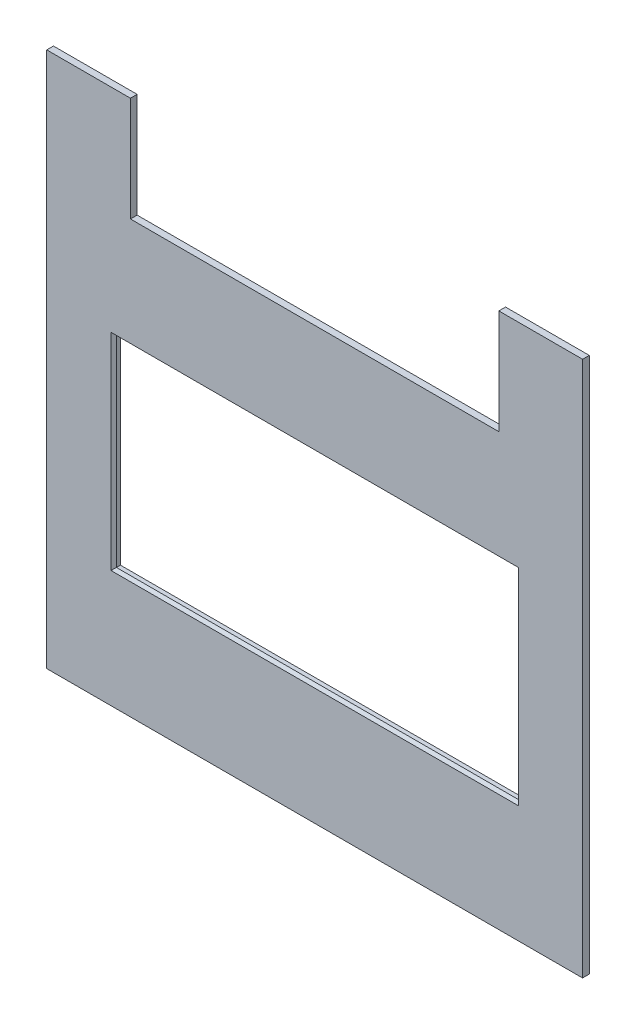
SolidWorks part; units mm, degrees
ref_plane "Plan de face" through (0, 0, 0) normal (0, 0, 1) x (1, 0, 0)
ref_plane "Plan de dessus" through (0, 0, 0) normal (0, 1, 0) x (1, 0, 0)
ref_plane "Plan de droite" through (0, 0, 0) normal (1, 0, 0) x (0, 0, -1)
sketch "Esquisse1" plane through (0, 0, 0) normal (0, 0, 1) x (1, 0, 0)
  line L1 (-200, 200) -> (200, 200)
  line L2 (-200, 200) -> (-200, -200)
  line L3 (-200, -200) -> (200, -200)
  line L4 (200, 200) -> (200, -200)
  line L5 (-200, 200) -> (200, -200) construction
  line L6 (-200, -200) -> (200, 200) construction
  point P0 (0, 0)
  dimension "D1" = 400
  dimension "D2" = 400
extrude "Boss.-Extru.1" add sketch "Esquisse1" along normal blind 5
sketch "Esquisse2" plane through (0, 0, 5) normal (0, 0, 1) x (1, 0, 0)
  line L0 (0, -230.2688) -> (0, 301.6087) construction
  line L1 (200, 200) -> (-200, 200) construction
  line L2 (-150, 39.43) -> (150, 39.43)
  line L3 (-150, 39.43) -> (-150, -110.59)
  line L4 (-150, -110.59) -> (150, -110.59)
  line L5 (150, 39.43) -> (150, -110.59)
  line L6 (-150, 39.43) -> (150, -110.59) construction
  line L7 (-150, -110.59) -> (150, 39.43) construction
  point P3 (0, -35.58)
  dimension "D1" = 235.58
  dimension "D2" = 300
  dimension "D3" = 150.02
extrude "Enlèv. mat.-Extru.1" cut sketch "Esquisse2" against normal blind 10
chamfer "Chanfrein1" distance 2 angle 45 4 edges at (0, 39.43, 5) (150, -35.58, 5) (0, -110.59, 5) (-150, -35.58, 5)
sketch "Esquisse3" plane through (0, 0, 5) normal (0, 0, 1) x (1, 0, 0)
  line L0 (0, 0) -> (0, 395.7632) construction
  line L2 (-137.5, 200) -> (137.5, 200)
  line L3 (-137.5, 200) -> (-137.5, 121.9316)
  line L4 (-137.5, 121.9316) -> (137.5, 121.9316)
  line L5 (137.5, 200) -> (137.5, 121.9316)
  line L6 (-137.5, 200) -> (137.5, 121.9316) construction
  line L7 (-137.5, 121.9316) -> (137.5, 200) construction
  line L8 (200, 200) -> (-200, 200) construction
  point P3 (0, 160.9658)
  dimension "D2" = 275
extrude "Enlèv. mat.-Extru.2" cut sketch "Esquisse3" against normal through all
